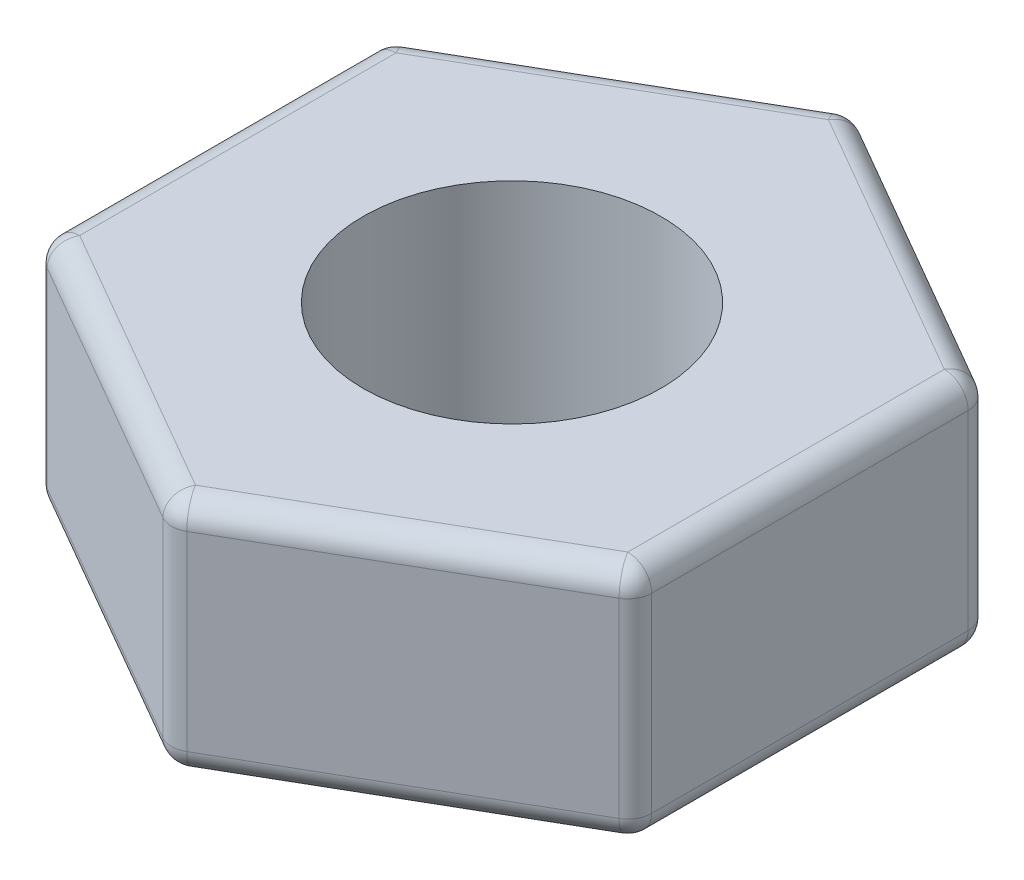
SolidWorks part; units mm, degrees
material "1023 Carbon Steel Sheet (SS)"
ref_plane "Front Plane" through (0, 0, 0) normal (0, 0, 1) x (1, 0, 0)
ref_plane "Top Plane" through (0, 0, 0) normal (0, 1, 0) x (1, 0, 0)
ref_plane "Right Plane" through (0, 0, 0) normal (1, 0, 0) x (0, 0, -1)
sketch "Sketch1" plane through (0, 0, 0) normal (0, 1, 0) x (1, 0, 0)
  line L1 (0, -2.8868) -> (2.5, -1.4434)
  line L2 (2.5, -1.4434) -> (2.5, 1.4434)
  line L3 (2.5, 1.4434) -> (0, 2.8868)
  line L4 (0, 2.8868) -> (-2.5, 1.4434)
  line L5 (-2.5, 1.4434) -> (-2.5, -1.4434)
  line L6 (-2.5, -1.4434) -> (0, -2.8868)
  circle A0 centre (0, 0) radius 2.5 construction
  circle A1 centre (0, 0) radius 1.25
  dimension "D2" = 2.5
  dimension "D1" = 5
extrude "Boss-Extrude1" add sketch "Sketch1" along normal blind 2
fillet "Fillet1" radius 0.2 18 edges at (1.25, 2, 2.1651) (1.25, 0, 2.1651) (-2.5, 2, 0) (-2.5, 0, 0) (-1.25, 2, -2.1651) (-2.5, 1, -1.4434) (-1.25, 0, -2.1651) (1.25, 2, -2.1651) (0, 1, -2.8868) (1.25, 0, -2.1651) (2.5, 1, 1.4434) (2.5, 2, 0) (2.5, 1, -1.4434) (2.5, 0, 0) (-2.5, 1, 1.4434) (-1.25, 2, 2.1651) (0, 1, 2.8868) (-1.25, 0, 2.1651)
